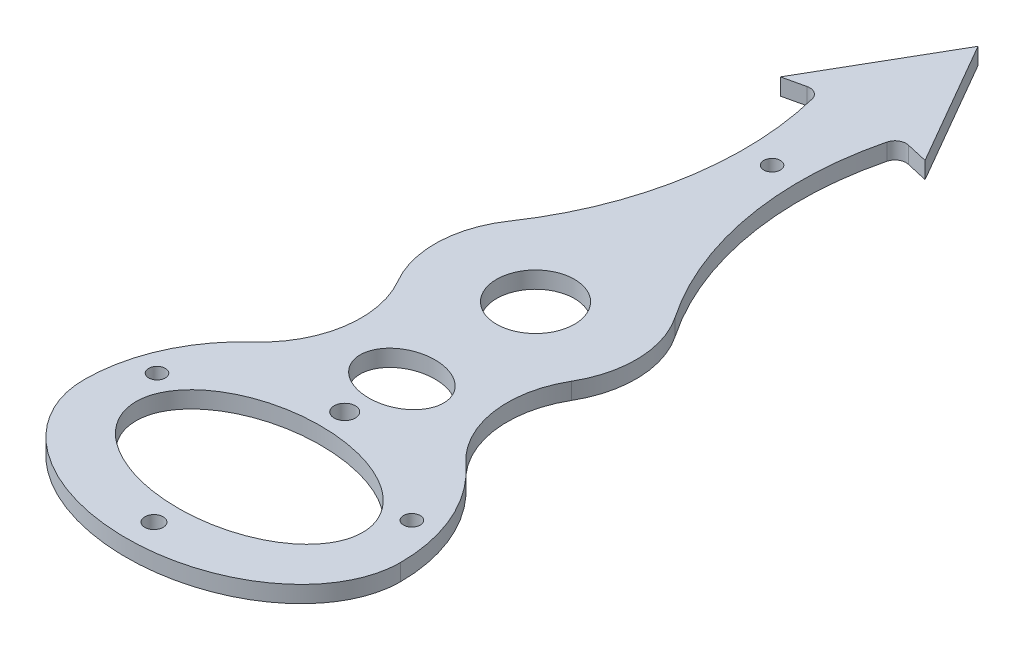
SolidWorks part; units mm, degrees
ref_plane "Front Plane" through (0, 0, 0) normal (0, 0, 1) x (1, 0, 0)
ref_plane "Top Plane" through (0, 0, 0) normal (0, 1, 0) x (1, 0, 0)
ref_plane "Right Plane" through (0, 0, 0) normal (1, 0, 0) x (0, 0, -1)
sketch "Sketch1" plane through (0, 0, 0) normal (0, 1, 0) x (1, 0, 0)
  line L0 (-12.9928, 56.9958) -> (0, 79.5)
  line L1 (0, 79.5) -> (12.9928, 56.9958)
  line L2 (-12.9928, 56.9958) -> (12.9928, 56.9958) construction
  line L3 (0, -68.5564) -> (0, 0) construction
  line L4 (-12.9928, 56.9958) -> (-9.0929, 57.8848)
  line L5 (-28.4436, -52.6898) -> (-28.4436, -68.5564) construction
  line L6 (0, 79.5) -> (0, -97) construction
  line L7 (12.9928, 56.9958) -> (9.0929, 57.8848)
  line L9 (1.35, -35.6282) -> (-1.35, -35.6282) construction
  line L10 (1.35, -35.6282) -> (1.35, -32.9282) construction
  line L11 (1.35, -32.9282) -> (-1.35, -32.9282) construction
  line L12 (-1.35, -35.6282) -> (-1.35, -32.9282) construction
  line L13 (0, -32.9282) -> (0, -35.6282) construction
  line L14 (1.35, -34.2782) -> (-1.35, -34.2782) construction
  circle A0 centre (0, 0) radius 80 construction
  arc A1 (-9.0929, 57.8848) -> (-6.7076, 56.4182) centre (-8.6483, 55.9349) cw
  circle A2 centre (0, -52.6898) radius 15.8666 construction
  circle A3 centre (0, -68.5564) radius 1.65
  arc A4 (-19.0837, -31.5984) -> (19.0837, -31.5984) centre (0, -52.6898) ccw construction
  circle A5 centre (0, 0) radius 18.0624 construction
  circle A6 centre (0, 0) radius 18.0624 construction
  circle A7 centre (0, 0) radius 58.458 construction
  circle A8 centre (0, -68.5564) radius 28.4436 construction
  arc A9 (-19.0837, -31.5984) -> (-15.6012, -9.1024) centre (-31.2024, -18.2047) ccw
  circle A10 centre (0, 0) radius 18.0624 construction
  arc A11 (19.0837, -31.5984) -> (15.6012, -9.1024) centre (31.2024, -18.2047) cw
  circle A12 centre (0, 0) radius 68.5564 construction
  arc A13 (-15.6012, -9.1024) -> (-14.944, 10.1452) centre (0, 0) cw
  arc A14 (-14.944, 10.1452) -> (-6.7076, 56.4182) centre (-62.5986, 42.4971) ccw
  arc A15 (15.6012, -9.1024) -> (14.944, 10.1452) centre (0, 0) ccw
  arc A16 (9.0929, 57.8848) -> (6.7076, 56.4182) centre (8.6483, 55.9349) ccw
  arc A17 (14.944, 10.1452) -> (6.7076, 56.4182) centre (62.5986, 42.4971) cw
  circle A18 centre (-22.8961, -45.1123) radius 4.3261 construction
  circle A19 centre (0, -34.2782) radius 21.0039 construction
  circle A20 centre (-22.8961, -45.1123) radius 1.5
  circle A21 centre (22.8961, -45.1123) radius 1.5
  circle A23 centre (0, 0) radius 7 construction
  circle A24 centre (0, 0) radius 7
  circle A25 centre (0, 42.4971) radius 1.5
  circle A27 centre (0, -34.2782) radius 1.9092
  circle A28 centre (0, -34.2782) radius 5.8346 construction
  arc A29 (-19.0837, -31.5984) -> (-28.4436, -52.6898) centre (0, -52.6898) ccw
  arc A30 (19.0837, -31.5984) -> (28.4436, -52.6898) centre (0, -52.6898) cw
  ellipse E0 centre (0, -52.6898) end of major axis (-28.4436, -52.6898) minor radius 20.8666 (28.4436, -52.6898) -> (-28.4436, -52.6898) cw
  point P2 (0, 80)
  point P4 (6.4964, 68.2479)
  point P8 (-5, 42.4971)
  point P19 (0, -70.2064)
  point P69 (0, -73.5564)
  point P76 (0, -73.5564)
  dimension "D4" = 2
  dimension "D5" = 3.3
  dimension "D6" = 3
  dimension "D7" = 2.7
  dimension "D1" = 0.5
  dimension "D2" = 4
  dimension "D3" = 5
  dimension "D8" = 5
extrude "Boss-Extrude1" add sketch "Sketch1" along normal blind 3
sketch "Sketch2" plane through (0, 3, 0) normal (0, 1, 0) x (1, 0, 0)
  line L0 (0, 79.5) -> (0, -97) construction
  circle A0 centre (0, -34.2782) radius 4.3261 construction
  circle A1 centre (0, -68.5564) radius 4.3261 construction
  circle A2 centre (22.8961, -45.1123) radius 4.3261 construction
  circle A3 centre (-22.8961, -45.1123) radius 4.3261 construction
  circle A4 centre (0, 0) radius 18.0624 construction
  ellipse E0 centre (0, -51.4173) end of major axis (20.3628, -51.4173) minor radius 12.813
  ellipse E1 centre (0, -24.0072) end of major axis (-7.5, -24.0072) minor radius 5.9448
  point P12 (-18.7935, -46.4849)
  point P18 (-18.7935, -46.4849)
  dimension "D1" = 15
extrude "Cut-Extrude1" cut sketch "Sketch2" against normal through all
